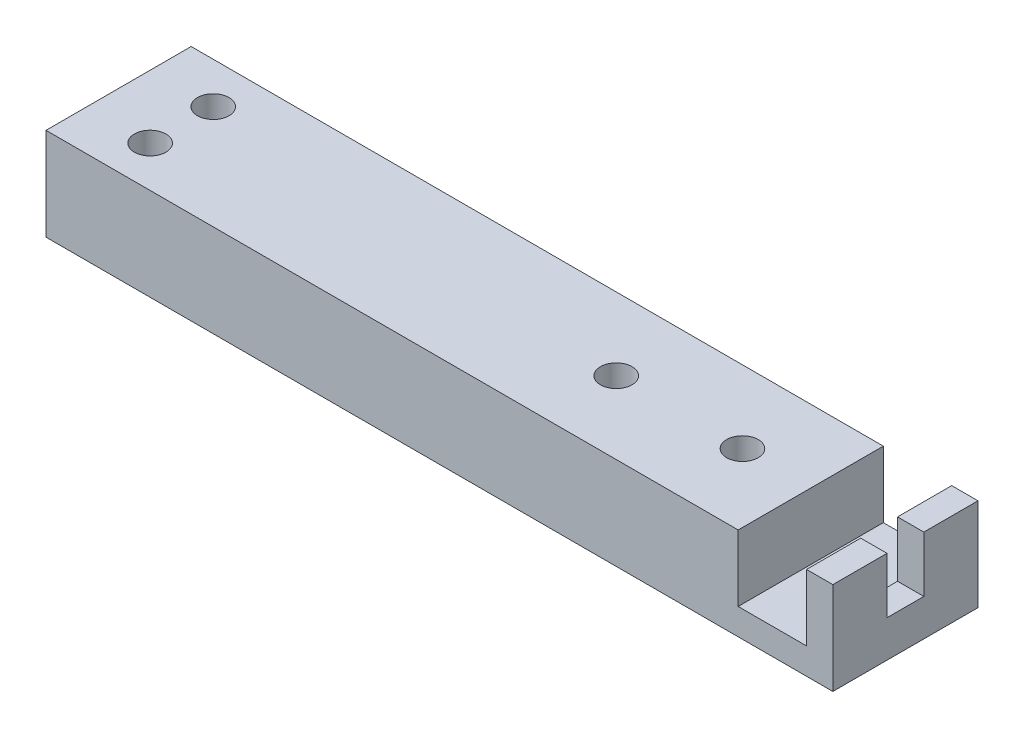
SolidWorks part; units mm, degrees
ref_plane "Front Plane" through (0, 0, 0) normal (0, 0, 1) x (1, 0, 0)
ref_plane "Top Plane" through (0, 0, 0) normal (0, 1, 0) x (1, 0, 0)
ref_plane "Right Plane" through (0, 0, 0) normal (1, 0, 0) x (0, 0, -1)
sketch "Sketch1" plane through (0, 0, 0) normal (0, 1, 0) x (1, 0, 0)
  line L1 (-37.4, -6.9) -> (37.4, -6.9)
  line L2 (-37.4, -6.9) -> (-37.4, 6.9)
  line L3 (-37.4, 6.9) -> (37.4, 6.9)
  line L4 (37.4, -6.9) -> (37.4, 6.9)
  line L5 (-37.4, -6.9) -> (37.4, 6.9) construction
  line L6 (-37.4, 6.9) -> (37.4, -6.9) construction
  point P0 (0, 0)
  dimension "D1" = 13.8
  dimension "D2" = 74.8
extrude "Boss-Extrude1" add sketch "Sketch1" along normal blind 8.8
sketch "Sketch2" plane through (0, 8.8, 0) normal (0, 1, 0) x (1, 0, 0)
  line L0 (-37.4, -6.9) -> (37.4, -6.9) construction
  line L1 (34.9, -6.9) -> (28.4, -6.9)
  line L2 (34.9, -6.9) -> (34.9, 6.9)
  line L3 (34.9, 6.9) -> (28.4, 6.9)
  line L4 (28.4, -6.9) -> (28.4, 6.9)
  line L5 (37.4, 6.9) -> (-37.4, 6.9) construction
  line L6 (37.4, -6.9) -> (37.4, 6.9) construction
  dimension "D1" = 2.5
  dimension "D2" = 6.5
extrude "Cut-Extrude1" cut sketch "Sketch2" against normal offset from surface (6.3 mm away) 2.5 up to face at (0, 0, 0)
sketch "Sketch3" plane through (37.4, 0, 0) normal (1, 0, 0) x (0, 0, -1)
  line L0 (-6.9, 8.8) -> (6.9, 8.8) construction
  line L1 (1.75, 8.8) -> (-1.75, 8.8)
  line L2 (1.75, 8.8) -> (1.75, 3.5)
  line L3 (1.75, 3.5) -> (-1.75, 3.5)
  line L4 (-1.75, 8.8) -> (-1.75, 3.5)
  line L5 (-6.9, 0) -> (6.9, 0) construction
  point P8 (0, 0)
  point P9 (0, 8.8)
  dimension "D1" = 3.5
  dimension "D2" = 3.5
extrude "Cut-Extrude2" cut sketch "Sketch3" against normal blind 2.8
sketch "Sketch4" plane through (0, 8.8, 0) normal (0, 1, 0) x (1, 0, 0)
  line L0 (-37.4, 6.9) -> (-37.4, -6.9) construction
  line L1 (28.4, 6.9) -> (28.4, -6.9) construction
  circle A0 centre (21.91, 0) radius 1.5
  circle A1 centre (9.91, 0) radius 1.5
  point P6 (-37.4, 0)
  dimension "D1" = 3
  dimension "D2" = 6.49
  dimension "D3" = 12
extrude "Cut-Extrude3" cut sketch "Sketch4" against normal blind 7
sketch "Sketch5" plane through (0, 8.8, 0) normal (0, 1, 0) x (1, 0, 0)
  line L0 (-31.4, 3) -> (-31.4, -3) construction
  line L1 (-37.4, 6.9) -> (-37.4, -6.9) construction
  circle A0 centre (-31.4, 3) radius 1.5
  circle A1 centre (-31.4, -3) radius 1.5
  point P6 (-37.4, 0)
  point P7 (-31.4, 0)
  dimension "D2" = 3
  dimension "D1" = 6
  dimension "D3" = 6
extrude "Cut-Extrude4" cut sketch "Sketch5" against normal blind 8
